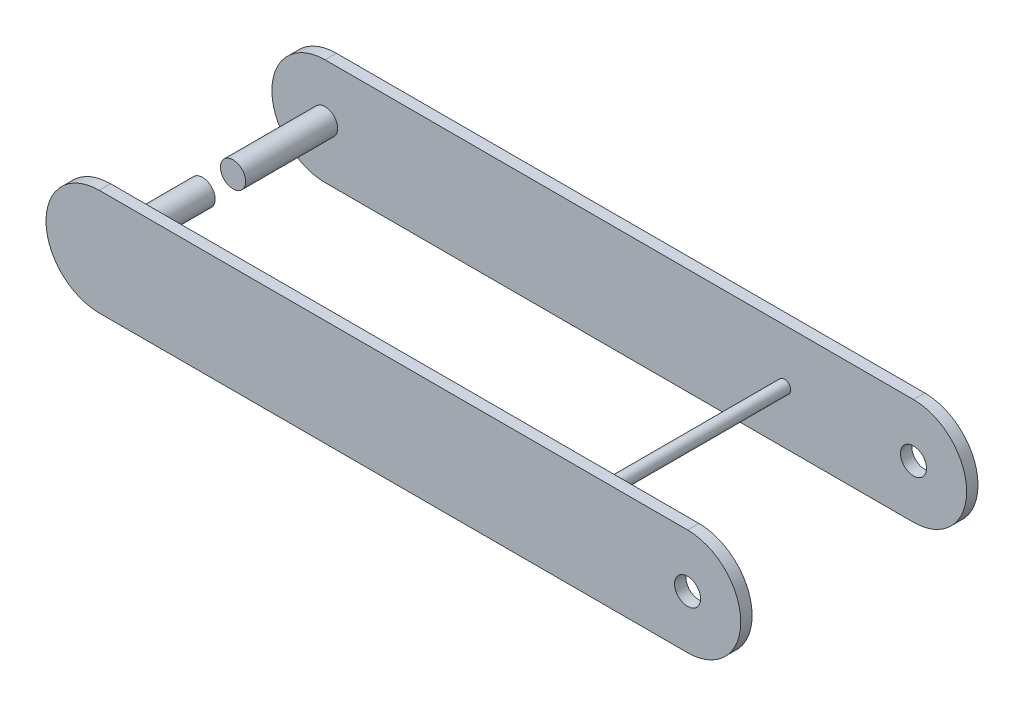
SolidWorks part; units mm, degrees
ref_plane "Front Plane" through (0, 0, 0) normal (0, 0, 1) x (1, 0, 0)
ref_plane "Top Plane" through (0, 0, 0) normal (0, 1, 0) x (1, 0, 0)
ref_plane "Right Plane" through (0, 0, 0) normal (1, 0, 0) x (0, 0, -1)
sketch "Sketch1" plane through (0, 0, 0) normal (0, 0, 1) x (1, 0, 0)
  line L0 (0, 0) -> (-149.5789, 0)
  line L1 (-149.5789, -50.6) -> (130.4211, -50.6)
  line L2 (130.4211, 0) -> (0, 0)
  arc A0 (-149.5789, 0) -> (-149.5789, -50.6) centre (-149.5789, -25.3) ccw
  arc A1 (130.4211, -50.6) -> (130.4211, 0) centre (130.4211, -25.3) ccw
  circle A2 centre (130.4211, -25.3) radius 6.2
  dimension "D1" = 280
  dimension "D3" = 12.4
  dimension "D2" = 50.6
extrude "Boss-Extrude1" add sketch "Sketch1" along normal blind 5.4
sketch "Sketch2" plane through (0, 0, 0) normal (0, 0, -1) x (-1, 0, 0)
  line L0 (-206.7904, -25.3) -> (233.7554, -25.3) construction
  line L1 (-155.4858, -25.3) -> (-68.9858, -25.3) construction
  circle A2 centre (-68.9858, -25.3) radius 3
  dimension "D1" = 86.5
  dimension "D2" = 6
extrude "Boss-Extrude3" add sketch "Sketch2" along normal blind 102.1
ref_plane "Plane1" through (0, 0, -102.1) normal (0, 0, -1) x (-1, 0, 0)
sketch "Sketch4" plane through (0, 0, -102.1) normal (0, 0, -1) x (-1, 0, 0)
  line L0 (-130.4211, 0) -> (149.5789, 0)
  line L1 (149.5789, -50.6) -> (-130.4211, -50.6)
  arc A0 (149.5789, 0) -> (149.5789, -50.6) centre (149.5789, -25.3) cw
  arc A1 (-130.4211, -50.6) -> (-130.4211, 0) centre (-130.4211, -25.3) cw
  circle A2 centre (-130.4211, -25.3) radius 6.2
  dimension "D1" = 12.4
extrude "Boss-Extrude4" add sketch "Sketch4" along normal blind 5.4
ref_plane "Plane2" through (0, 0, -51.05) normal (0, 0, 1) x (1, 0, 0)
sketch "Sketch5" plane through (0, 0, -102.1) normal (0, 0, 1) x (1, 0, 0)
  line L0 (-149.5789, 0) -> (-149.5789, -50.6) construction
  line L1 (-149.5789, -50.6) -> (130.4211, -50.6) construction
  line L2 (-174.8789, -25.3) -> (-58.2594, -25.3) construction
  arc A0 (-149.5789, 0) -> (-149.5789, -50.6) centre (-149.5789, -25.3) ccw construction
  circle A1 centre (-149.5789, -25.3) radius 6
  dimension "D1" = 12
extrude "Boss-Extrude5" add sketch "Sketch5" along normal blind 43.8
mirror "Mirror1" about plane through (0, 0, -51.05) normal (0, 0, 1) of "Boss-Extrude5"
